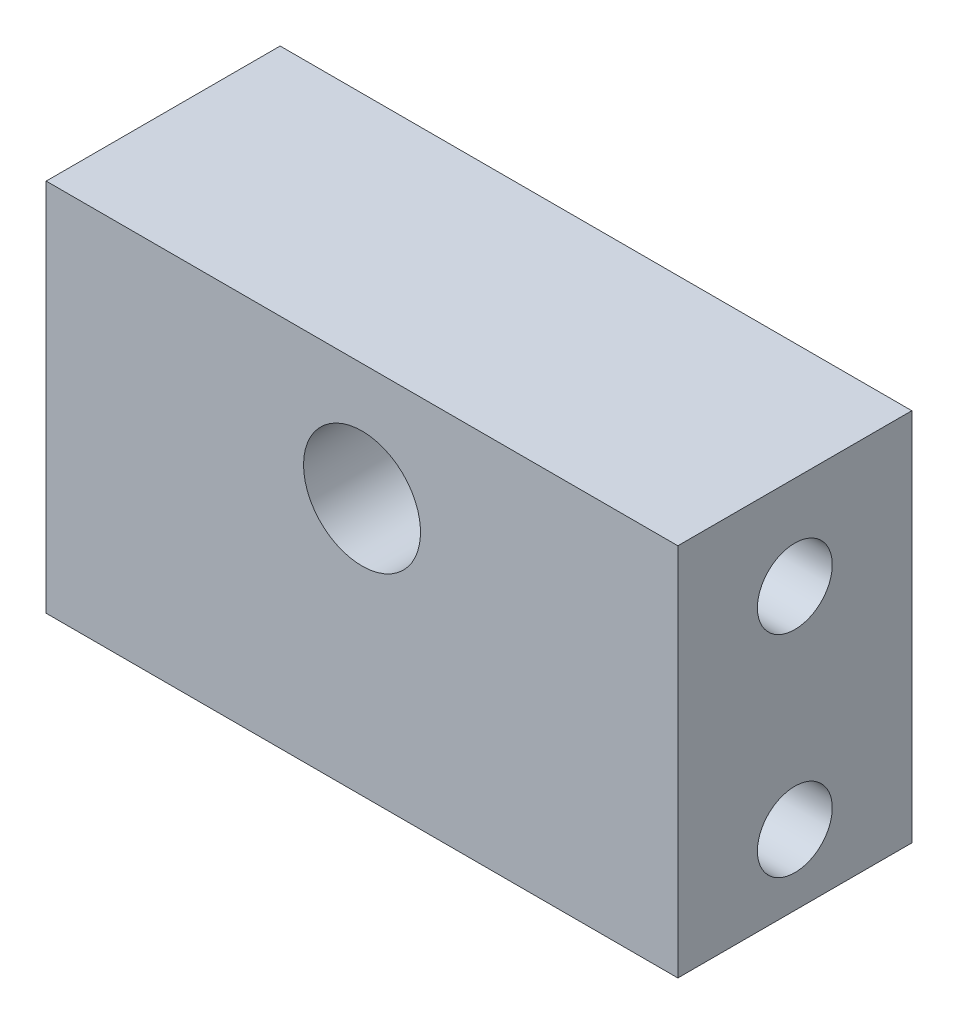
SolidWorks part; units mm, degrees
material "AISI 4130 Acier normalisé à 870C"
ref_plane "Plan de face" through (0, 0, 0) normal (0, 0, 1) x (1, 0, 0)
ref_plane "Plan de dessus" through (0, 0, 0) normal (0, 1, 0) x (1, 0, 0)
ref_plane "Plan de droite" through (0, 0, 0) normal (1, 0, 0) x (0, 0, -1)
sketch "Esquisse1" plane through (0, 0, 0) normal (0, 0, 1) x (1, 0, 0)
  line L1 (0, 0) -> (13.5, 0)
  line L2 (0, 0) -> (0, 8)
  line L3 (0, 8) -> (13.5, 8)
  line L4 (13.5, 0) -> (13.5, 8)
  dimension "D1" = 13.5
  dimension "D2" = 8
extrude "Boss.-Extru.1" add sketch "Esquisse1" along normal blind 5
hole_wizard "Trou pour taraudage pour trou taraudé M21" positions "Esquisse2" profile "Esquisse4" hole size "M2" standard "ISO" end condition through all
sketch "Esquisse2" plane through (0, 0, 0) normal (-1, 0, 0) x (0, 0, 1)
  line L4 (2.5, 6) -> (2.5, 7.5239) construction
  line L6 (0, 8) -> (0, 0) construction
  line L7 (5, 8) -> (5, 0) construction
  line L8 (5, 8) -> (0, 8) construction
  point P0 (2.5, 6)
  point P21 (2.5, 8)
  point P22 (2.5, 1.5)
  point P27 (0, 0)
  point P28 (2.5, 2)
  dimension "D1" = 2
  dimension "D2" = 4.5
sketch "Esquisse4" plane through (0, 6, 2.5) normal (0, 1, 0) x (0, 0, 1)
  line L0 (0, 0) -> (0, 13.5)
  line L1 (0, 13.5) -> (0.8, 13.5)
  line L2 (0.8, 13.5) -> (0.8, 0)
  line L5 (0.8, 0) -> (0, 0)
  line L11 (0, -6.35) -> (0, 107.95) construction
  dimension "Diamètre du perçage jusqu'au prochain" = 1.6
  dimension "Profondeur du perçage jusqu'au prochain" = 13.5
hole_wizard "Trou pour taraudage pour trou taraudé M32" positions "Esquisse5" profile "Esquisse6" hole size "M3" standard "ISO"
sketch "Esquisse5" plane through (0, 0, 5) normal (0, 0, 1) x (1, 0, 0)
  line L0 (6.75, 8) -> (6.75, 4.339) construction
  line L1 (13.5, 8) -> (0, 8) construction
  point P0 (6.75, 5)
  dimension "D1" = 3
sketch "Esquisse6" plane through (6.75, 5, 5) normal (1, 0, 0) x (0, -1, 0)
  line L0 (0, 0) -> (0, 5)
  line L1 (0, 5) -> (1.25, 5)
  line L2 (1.25, 5) -> (1.25, 0)
  line L5 (1.25, 0) -> (0, 0)
  line L11 (0, -6.35) -> (0, 107.95) construction
  dimension "Diamètre du perçage jusqu'au prochain" = 2.5
  dimension "Profondeur du perçage jusqu'au prochain" = 5
hole_wizard "Kernloch für M2 Gewinde1" positions "Skizze1" profile "Skizze2" hole size "M2" standard "ISO"
sketch "Skizze1" plane through (0, 0, 0) normal (-1, 0, 0) x (0, 0, 1)
  line L0 (2.5, 0) -> (2.5, 8) construction
  line L1 (5, 0) -> (0, 0) construction
  line L2 (5, 8) -> (0, 8) construction
  point P0 (1.25, 3)
  point P2 (3.75, 1.5)
  dimension "D1" = 1.25
  dimension "D2" = 1.25
  dimension "D3" = 1.5
  dimension "D4" = 1.5
sketch "Skizze2" plane through (0, 3, 1.25) normal (0, 1, 0) x (0, 0, 1)
  line L0 (0, 0) -> (0, 13.9807)
  line L1 (0, 13.9807) -> (0.8, 13.5)
  line L2 (0.8, 13.5) -> (0.8, 0)
  line L5 (0.8, 0) -> (0, 0)
  line L10 (0, 13.9807) -> (-0.8, 13.5) construction
  line L11 (0, -6.35) -> (0, 107.95) construction
  dimension "Bohrerdurchmesser" = 1.6
  dimension "Bohrungstiefe" = 13.5
  dimension "Spitzenwinkel" = 118
hole_wizard "Kernloch für M3 Gewinde1" positions "Skizze3" profile "Skizze4" hole size "M3" standard "ISO"
sketch "Skizze3" plane through (0, 0, 0) normal (0, 0, -1) x (-1, 0, 0)
  line L0 (-13.5, 8) -> (0, 8) construction
  line L1 (0, 8) -> (0, 0) construction
  point P0 (-6.75, 5.5)
  dimension "D1" = 2.5
  dimension "D2" = 6.75
sketch "Skizze4" plane through (6.75, 5.5, 0) normal (1, 0, 0) x (0, 1, 0)
  line L0 (0, 0) -> (0, 5.7511)
  line L1 (0, 5.7511) -> (1.25, 5)
  line L2 (1.25, 5) -> (1.25, 0)
  line L5 (1.25, 0) -> (0, 0)
  line L10 (0, 5.7511) -> (-1.25, 5) construction
  line L11 (0, -6.35) -> (0, 107.95) construction
  dimension "Bohrerdurchmesser" = 2.5
  dimension "Bohrungstiefe" = 5
  dimension "Spitzenwinkel" = 118
